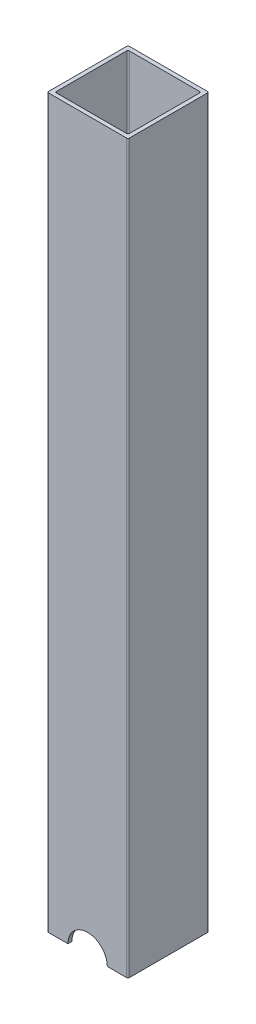
SolidWorks part; units mm, degrees
ref_plane "Front Plane" through (0, 0, 0) normal (0, 0, 1) x (1, 0, 0)
ref_plane "Top Plane" through (0, 0, 0) normal (0, 1, 0) x (1, 0, 0)
ref_plane "Right Plane" through (0, 0, 0) normal (1, 0, 0) x (0, 0, -1)
sketch "Sketch1" plane through (0, 0, 0) normal (0, 1, 0) x (1, 0, 0)
  line L1 (0, 0) -> (25.4, 0)
  line L2 (0, 0) -> (0, 25.4)
  line L3 (0, 25.4) -> (25.4, 25.4)
  line L4 (25.4, 0) -> (25.4, 25.4)
  line L5 (1.2446, 1.2446) -> (24.1554, 1.2446)
  line L6 (1.2446, 1.2446) -> (1.2446, 24.1554)
  line L7 (1.2446, 24.1554) -> (24.1554, 24.1554)
  line L8 (24.1554, 1.2446) -> (24.1554, 24.1554)
  dimension "D1" = 25.4
  dimension "D2" = 1.2446
  dimension "D3" = 1.2446
  dimension "D4" = 1.2446
extrude "Boss-Extrude1" add sketch "Sketch1" against normal blind 228.6
fillet "Fillet1" radius 0.4064 8 edges at (0, -114.3, 0) (1.2446, -114.3, -1.2446) (24.1554, -114.3, -1.2446) (25.4, -114.3, 0) (25.4, -114.3, -25.4) (24.1554, -114.3, -24.1554) (1.2446, -114.3, -24.1554) (0, -114.3, -25.4)
sketch "Sketch2" plane through (0, 0, -25.4) normal (0, 0, -1) x (-1, 0, 0)
  line L0 (-24.9936, -228.6) -> (-0.4064, -228.6) construction
  circle A0 centre (-12.7, -228.6) radius 6.1913
  dimension "D1" = 12.3825
extrude "Cut-Extrude1" cut sketch "Sketch2" against normal through all
